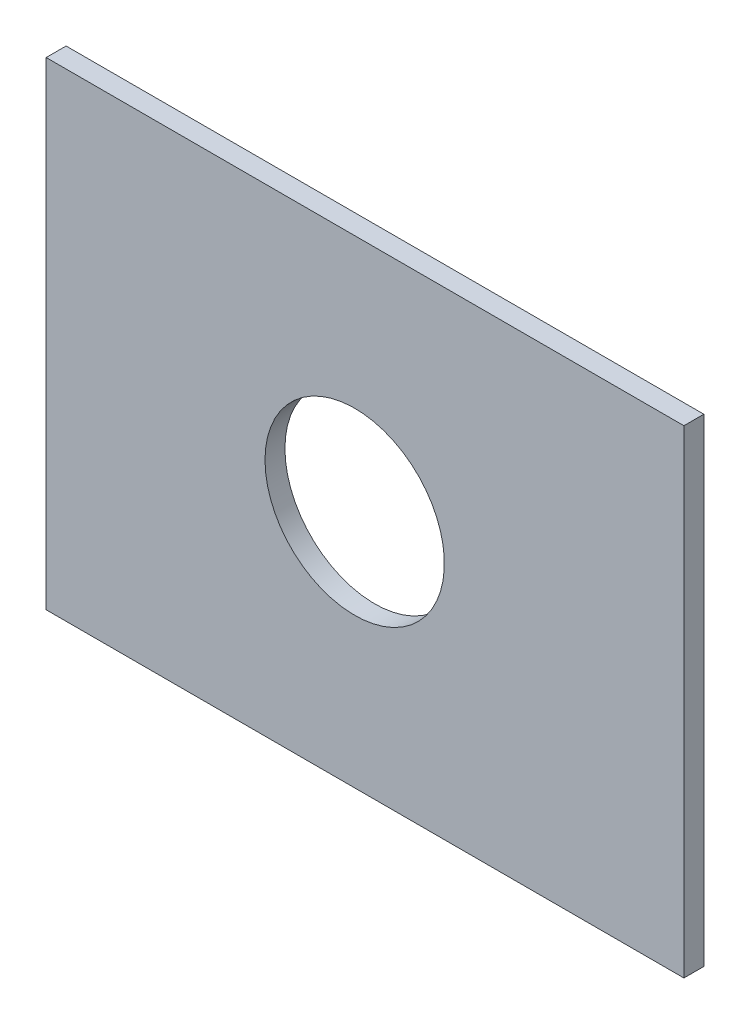
SolidWorks part; units mm, degrees
material "6061-T6 (SS)"
ref_plane "Front Plane" through (0, 0, 0) normal (0, 0, 1) x (1, 0, 0)
ref_plane "Top Plane" through (0, 0, 0) normal (0, 1, 0) x (1, 0, 0)
ref_plane "Right Plane" through (0, 0, 0) normal (1, 0, 0) x (0, 0, -1)
sketch "Sketch4" plane through (0, 0, -1436.3193) normal (0, 0, -1) x (-1, 0, 0)
  line L1 (2168.7152, 147.8891) -> (2270.3152, 147.8891)
  line L2 (2168.7152, 147.8891) -> (2168.7152, 224.0891)
  line L3 (2168.7152, 224.0891) -> (2270.3152, 224.0891)
  line L4 (2270.3152, 147.8891) -> (2270.3152, 224.0891)
  line L5 (2221.1651, 147.8891) -> (2221.1651, 224.0891) construction
  circle A4 centre (2221.1651, 185.9891) radius 14.2875
  point P0 (2221.1651, 185.9891)
  point P13 (2221.1651, 185.9891)
  dimension "D1" = 76.2
  dimension "D2" = 101.6
extrude "Boss-Extrude1" add sketch "Sketch4" along normal blind 3.175
